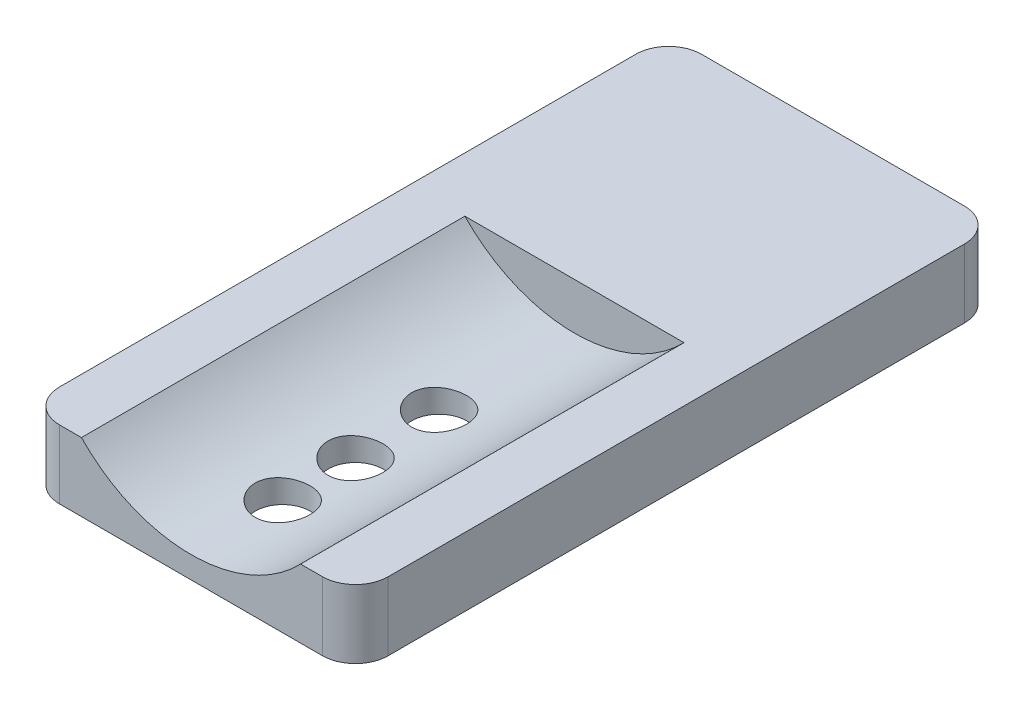
SolidWorks part; units mm, degrees
ref_plane "Front Plane" through (0, 0, 0) normal (0, 0, 1) x (1, 0, 0)
ref_plane "Top Plane" through (0, 0, 0) normal (0, 1, 0) x (1, 0, 0)
ref_plane "Right Plane" through (0, 0, 0) normal (1, 0, 0) x (0, 0, -1)
sketch "Sketch1" plane through (0, 0, 0) normal (1, 0, 0) x (0, 0, -1)
  line L0 (0, 0) -> (58.6, 0)
  line L1 (58.6, 0) -> (58.6, 6.25)
  line L2 (58.6, 6.25) -> (0, 6.25)
  line L3 (0, 6.25) -> (0, 0)
  line L4 (0, 3.125) -> (58.6, 3.125) construction
  dimension "D1" = 58.6
  dimension "D2" = 6.25
extrude "Boss-Extrude1" add sketch "Sketch1" along normal blind 30
sketch "Sketch2" plane through (0, 0, 0) normal (0, 0, 1) x (1, 0, 0)
  line L0 (30, 6.25) -> (0, 6.25) construction
  line L1 (5, 6.25) -> (25, 6.25)
  line L2 (5, 6.25) -> (25, 6.25)
  arc A0 (5, 6.25) -> (25, 6.25) centre (15, 15.8897) ccw
  point P3 (15, 2)
  dimension "D1" = 5
  dimension "D2" = 5
  dimension "D3" = 4.25
extrude "Cut-Extrude1" cut sketch "Sketch2" against normal blind 35 and the other way through all contours A0
sketch "Sketch4" plane through (0, 0, 0) normal (0, -1, 0) x (1, 0, 0)
  line L1 (22.8, -38.1) -> (22.8, -5)
  line L2 (22.8, -5) -> (7.2, -5)
  line L3 (7.2, -5) -> (7.2, -38.1)
  line L4 (30, -58.6) -> (0, -58.6) construction
  line L5 (22.8, -38.1) -> (22.8, -48.6)
  line L6 (7.2, -38.1) -> (22.8, -38.1)
  line L10 (22.8, -48.6) -> (7.2, -48.6)
  line L11 (7.2, -48.6) -> (7.2, -38.1)
  line L13 (30, 0) -> (0, 0) construction
  circle A0 centre (15, -8.37) radius 2.5
  circle A1 centre (15, -15.02) radius 2.5
  circle A2 centre (15, -22.65) radius 2.5
  point P7 (15, -58.6)
  point P12 (15, -5)
  point P20 (15, 0)
  dimension "D4" = 5
  dimension "D8" = 5
  dimension "D9" = 5
  dimension "D2" = 10.5
  dimension "D3" = 43.6
  dimension "D5" = 5
  dimension "D7" = 15.6
  dimension "D10" = 3.37
  dimension "D11" = 10.02
  dimension "D12" = 17.65
extrude "Cut-Extrude2" cut sketch "Sketch4" against normal blind 4
sketch "Sketch5" plane through (0, 0, -58.6) normal (0, 0, -1) x (-1, 0, 0)
  line L9 (-30, 0) -> (0, 0) construction
  line L11 (-30, 6.25) -> (0, 6.25) construction
  line L13 (-9.85, 0.95) -> (-20.15, 0.95)
  line L15 (-20.15, 5.3) -> (-9.85, 5.3)
  line L18 (-9.85, 5.3) -> (-9.85, 0.95)
  line L19 (-20.15, 0.95) -> (-17.975, 3.125)
  line L20 (-17.975, 3.125) -> (-20.15, 5.3)
  point P5 (-15, 0.95)
  point P10 (-15, 0)
  point P12 (-9.85, 3.125)
  dimension "D1" = 10.3
  dimension "D2" = 0.95
  dimension "D3" = 0.95
extrude "Cut-Extrude3" cut sketch "Sketch5" against normal blind 9.5
sketch "Sketch6" plane through (0, 0, 0) normal (0, -1, 0) x (1, 0, 0)
  line L1 (7.2, -38.1) -> (22.8, -38.1)
  line L2 (7.2, -38.1) -> (7.2, -37.1)
  line L3 (7.2, -37.1) -> (22.8, -37.1)
  line L4 (22.8, -38.1) -> (22.8, -37.1)
  line L5 (22.8, -48.6) -> (7.2, -48.6)
  line L6 (22.8, -48.6) -> (22.8, -49.1)
  line L7 (22.8, -49.1) -> (7.2, -49.1)
  line L8 (7.2, -48.6) -> (7.2, -49.1)
  dimension "D1" = 0.5
  dimension "D2" = 1
extrude "Cut-Extrude4" cut sketch "Sketch6" against normal up to surface (4 mm away) up to face at (15, 4, -43.35)
fillet "Fillet1" radius 3 4 edges at (0, 3.125, 0) (0, 3.125, -58.6) (30, 3.125, -58.6) (30, 3.125, 0)
sketch "Sketch7" plane through (0, 0, 0) normal (0, -1, 0) x (1, 0, 0)
  line L0 (0, -3) -> (0, -55.6) construction
  line L1 (27, -58.6) -> (3, -58.6) construction
  line L2 (15, -58.6) -> (15, 0) construction
  line L3 (27, 0) -> (3, 0) construction
  line L4 (30, -29.3) -> (0, -29.3) construction
  line L5 (30, -3) -> (30, -55.6) construction
  circle A0 centre (3, -55.6) radius 1.65
  circle A1 centre (27, -55.6) radius 1.65
  circle A2 centre (27, -3) radius 1.65
  circle A3 centre (3, -3) radius 1.65
  dimension "D1" = 3.3
  dimension "D2" = 3
  dimension "D3" = 3
extrude "Cut-Extrude5" cut sketch "Sketch7" against normal blind 3
